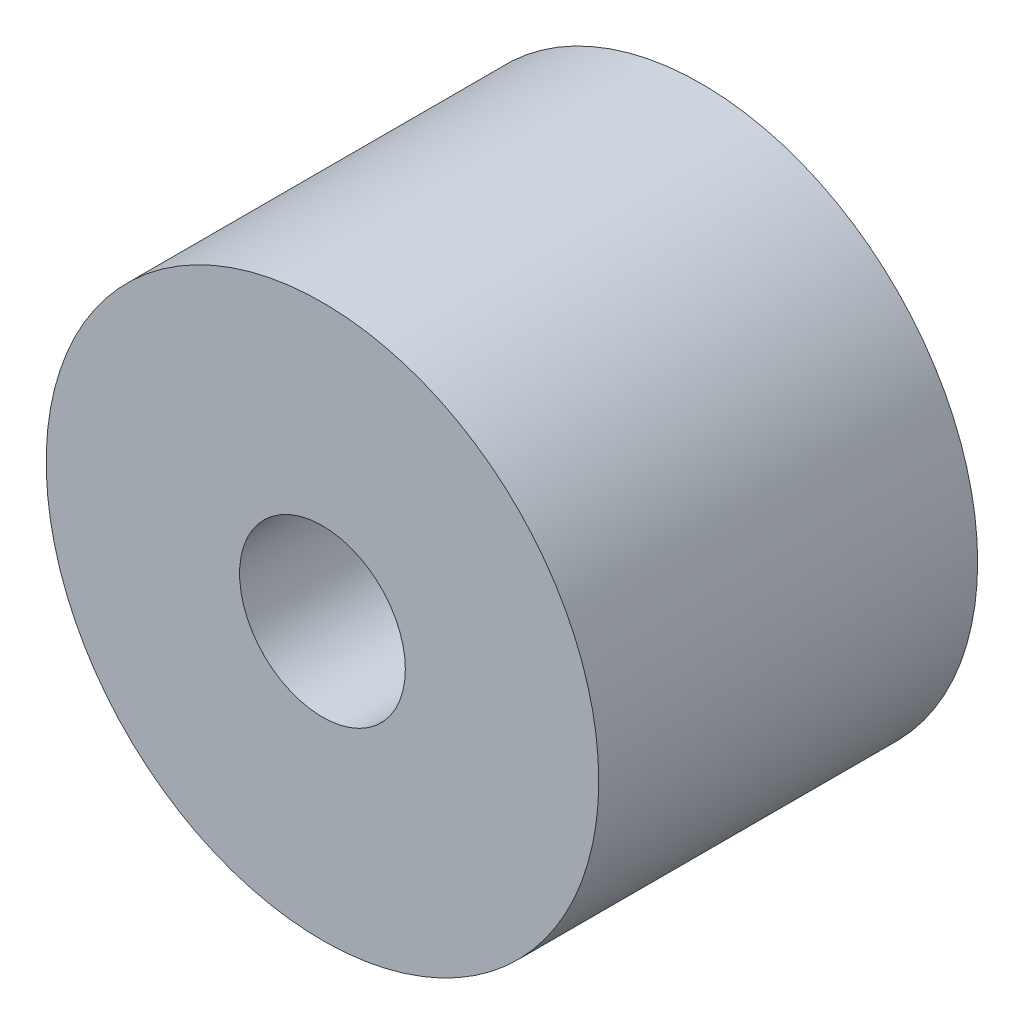
SolidWorks part; units mm, degrees
ref_plane "Спереди" through (0, 0, 0) normal (0, 0, 1) x (1, 0, 0)
ref_plane "Сверху" through (0, 0, 0) normal (0, 1, 0) x (1, 0, 0)
ref_plane "Справа" through (0, 0, 0) normal (1, 0, 0) x (0, 0, -1)
sketch "Эскиз1" plane through (0, 0, 0) normal (0, 0, 1) x (1, 0, 0)
  circle A0 centre (0, 0) radius 5.25
  circle A1 centre (0, 0) radius 17.5
  dimension "D1" = 10.5
  dimension "D2" = 35
extrude "Вытянуть1" add sketch "Эскиз1" along normal blind 24
